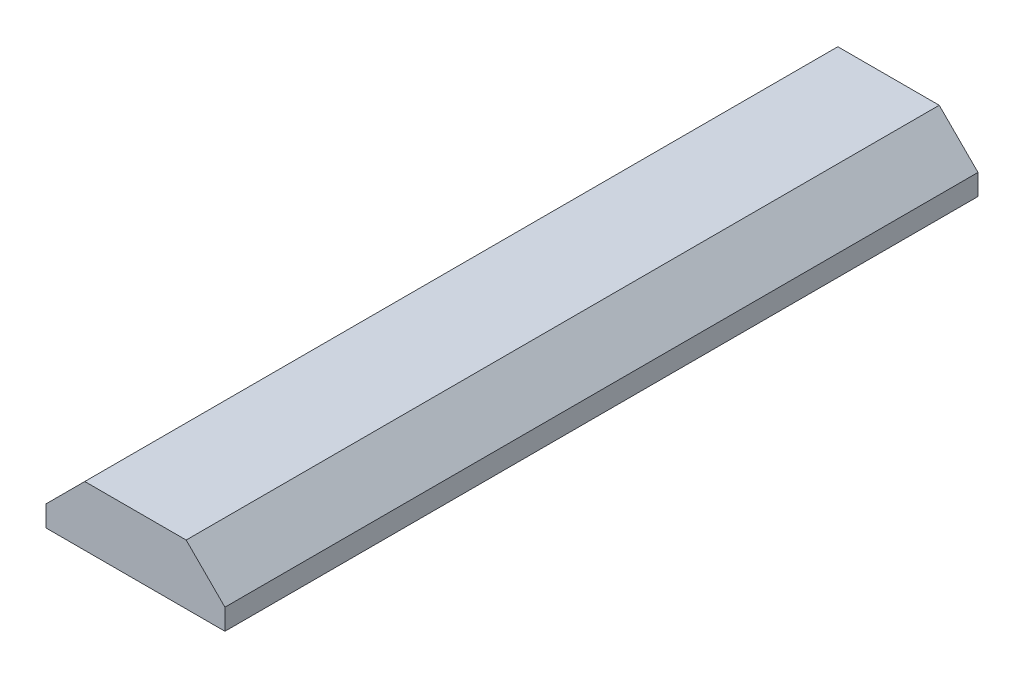
SolidWorks part; units mm, degrees
ref_plane "Ebene vorne" through (0, 0, 0) normal (0, 0, 1) x (1, 0, 0)
ref_plane "Ebene oben" through (0, 0, 0) normal (0, 1, 0) x (1, 0, 0)
ref_plane "Ebene rechts" through (0, 0, 0) normal (1, 0, 0) x (0, 0, -1)
sketch "Skizze1" plane through (0, 0, 0) normal (0, 0, 1) x (1, 0, 0)
  line L0 (0, 0) -> (0, 23680.6173) construction
  line L1 (3.4, 1.8089) -> (-3.4, 1.8089)
  line L2 (-3.4, 1.8089) -> (-6, -0.7911)
  line L3 (-6, -0.7911) -> (-6, -2.1911)
  line L4 (-6, -2.1911) -> (6, -2.1911)
  line L5 (6, -0.7911) -> (6, -2.1911)
  line L6 (3.4, 1.8089) -> (6, -0.7911)
  point P9 (0, -2.1911)
  point P11 (0, 1.8089)
  dimension "D1" = 3.4
  dimension "D2" = 6
  dimension "D3" = 4
  dimension "D4" = 135
extrude "Aufsatz-Linear austragen1" add sketch "Skizze1" along normal blind 50.5 contours L1 L2 L3 L4 L5 L6
